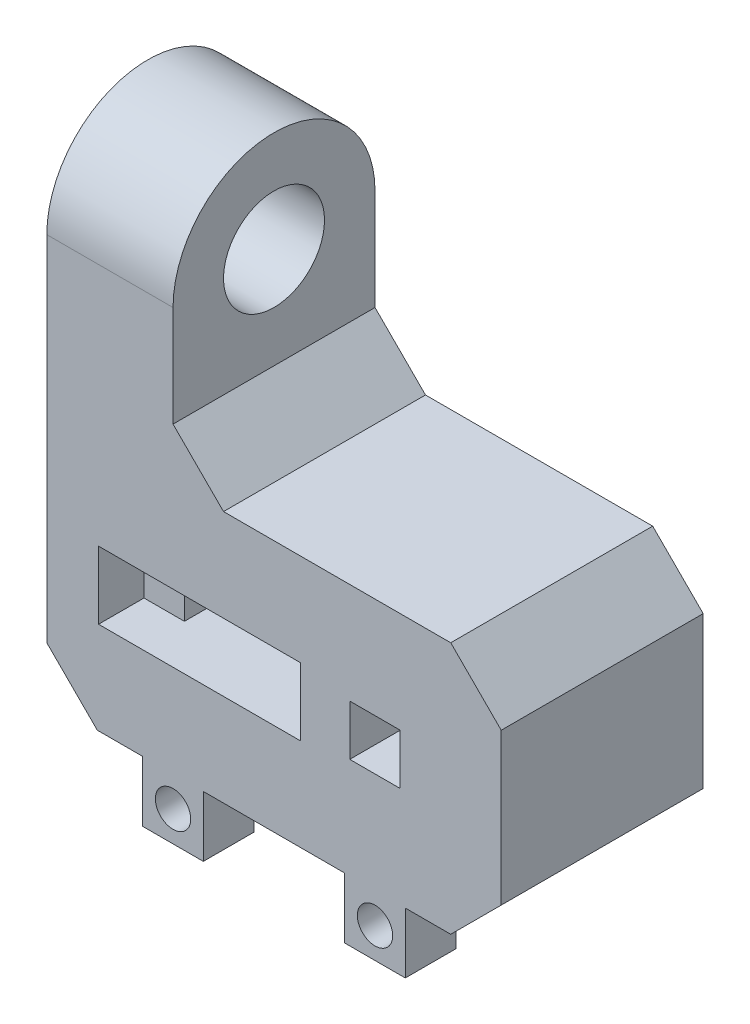
SolidWorks part; units mm, degrees
ref_plane "Front Plane" through (0, 0, 0) normal (0, 0, 1) x (1, 0, 0)
ref_plane "Top Plane" through (0, 0, 0) normal (0, 1, 0) x (1, 0, 0)
ref_plane "Right Plane" through (0, 0, 0) normal (1, 0, 0) x (0, 0, -1)
sketch "Sketch1" plane through (0, 0, 0) normal (0, 0, 1) x (1, 0, 0)
  line L1 (-90, 50) -> (0, 50)
  line L2 (-90, 50) -> (-90, 0)
  line L3 (-90, 0) -> (0, 0)
  line L4 (0, 50) -> (0, 0)
  dimension "D1" = 90
  dimension "D2" = 50
extrude "Boss-Extrude1" add sketch "Sketch1" along normal blind 40
sketch "Sketch19" plane through (0, 0, 40) normal (0, 0, 1) x (1, 0, 0)
  line L0 (-65, 25) -> (-25, 25) construction
  line L1 (-65, 25) -> (-65, 0) construction
  line L2 (-90, 0) -> (0, 0) construction
  line L3 (-65, 25) -> (-65, 50) construction
  line L4 (0, 50) -> (-90, 50) construction
  line L7 (-25, 25) -> (0, 25) construction
  line L8 (0, 0) -> (0, 50) construction
  line L9 (-65, 25) -> (-90, 25) construction
  line L10 (-90, 50) -> (-90, 0) construction
  circle A0 centre (-65, 25) radius 20
  circle A1 centre (-25, 25) radius 20
  point P10 (0, 0)
  point P11 (0, 0)
  dimension "D1" = 40
  dimension "D2" = 40
sketch "Sketch21" plane through (0, 0, 40) normal (0, 0, 1) x (1, 0, 0)
  line L1 (-30, 30) -> (-20, 30)
  line L2 (-30, 30) -> (-30, 20)
  line L3 (-30, 20) -> (-20, 20)
  line L4 (-20, 30) -> (-20, 20)
  circle A0 centre (-25, 25) radius 5
  dimension "D1" = 10
extrude "Cut-Extrude10" cut sketch "Sketch21" against normal up to surface (40 mm away) contours A0 | A0 L1 L2 | A0 L2 L3 | A0 L3 L4 | A0 L4 L1 up to face at (-45, 25, 0)
sketch "Sketch22" plane through (0, 0, 40) normal (0, 0, 1) x (1, 0, 0)
  line L0 (-79.75, 25) -> (-90, 25) construction
  line L1 (-79.75, 18.3) -> (-39.75, 18.3)
  line L2 (-79.75, 18.3) -> (-79.75, 31.7)
  line L3 (-79.75, 31.7) -> (-39.75, 31.7)
  line L4 (-39.75, 18.3) -> (-39.75, 31.7)
  line L5 (-59.75, 18.3) -> (-59.75, 0) construction
  line L6 (-90, 0) -> (0, 0) construction
  line L7 (-59.75, 31.7) -> (-59.75, 50) construction
  line L8 (0, 50) -> (-90, 50) construction
  point P16 (-59.75, 18.3)
  dimension "D1" = 10.25
  dimension "D3" = 13.4
  dimension "D4" = 40
extrude "Cut-Extrude11" cut sketch "Sketch22" against normal blind 9
sketch "Sketch24" plane through (0, 0, 31) normal (0, 0, 1) x (1, 0, 0)
  line L0 (-79.75, 18.3) -> (-39.75, 18.3) construction
  line L1 (-71.75, 18.3) -> (-47.75, 18.3)
  line L2 (-71.75, 18.3) -> (-71.75, 31.7)
  line L3 (-71.75, 31.7) -> (-47.75, 31.7)
  line L4 (-47.75, 18.3) -> (-47.75, 31.7)
  line L5 (-39.75, 31.7) -> (-79.75, 31.7) construction
  line L6 (-39.75, 25) -> (-47.75, 25) construction
  line L7 (-39.75, 18.3) -> (-39.75, 31.7) construction
  line L8 (-71.75, 25) -> (-79.75, 25) construction
  line L10 (-79.75, 31.7) -> (-79.75, 18.3) construction
  dimension "D1" = 24
extrude "Cut-Extrude12" cut sketch "Sketch24" against normal up to surface (31 mm away) up to face at (-45, 25, 0)
sketch "Sketch25" plane through (0, 0, 31) normal (0, 0, 1) x (1, 0, 0)
  line L0 (-46.25, 25) -> (-73.25, 25) construction
  circle A0 centre (-73.25, 25) radius 1.1
  circle A1 centre (-46.25, 25) radius 1.1
  dimension "D1" = 2.2
extrude "Cut-Extrude13" cut sketch "Sketch25" against normal up to surface (31 mm away) up to face at (-59.75, 25, 0)
ref_plane "Plane1" through (-45, 0, 0) normal (-1, 0, 0) x (0, 0, 1)
sketch "Sketch31" plane through (0, 50, 0) normal (0, 1, 0) x (1, 0, 0)
  line L0 (0, 0) -> (-90, 0) construction
  line L1 (-25, 0) -> (0, 0)
  line L2 (-25, 0) -> (-25, -40)
  line L3 (-25, -40) -> (0, -40)
  line L4 (0, 0) -> (0, -40)
  line L5 (-65, -40) -> (-90, -40) construction
  line L6 (-90, 0) -> (-65, 0)
  line L7 (-90, 0) -> (-90, -40)
  line L8 (-90, -40) -> (-65, -40)
  line L9 (-65, 0) -> (-65, -40)
  line M5 (0, 0) -> (-90, 0)
  line M6 (-90, 0) -> (-90, -40)
  line M7 (-90, -40) -> (0, -40)
  dimension "D1" = 25
extrude "Boss-Extrude2" add sketch "Sketch31" along normal blind 50 contours L9 M5 M6 M7
sketch "Sketch32" plane through (-65, 0, 0) normal (1, 0, 0) x (0, 0, -1)
  line L0 (0, 100) -> (-40, 100) construction
  line L1 (-40, 100) -> (-40, 50) construction
  line L2 (0, 100) -> (0, 50) construction
  circle A0 centre (-20, 80) radius 20
  circle A1 centre (-20, 80) radius 10
  line M3 (0, 50) -> (0, 100)
  line M4 (0, 100) -> (-40, 100)
  line M5 (-40, 100) -> (-40, 50)
  dimension "D1" = 20
extrude "Cut-Extrude15" cut sketch "Sketch32" against normal up to surface (25 mm away) contours A0 M4 M5 | A0 M3 M4 | A1 up to face at (-90, 50, 20)
chamfer "Chamfer1" distance 10 angle 45 4 edges at (0, 0, 20) (-90, 0, 20) (-65, 50, 20) (0, 50, 20)
sketch "Sketch35" plane through (-90, 0, 0) normal (-1, 0, 0) x (0, 0, 1)
  line L0 (22.1864, 25) -> (40, 25) construction
  line L1 (40, 5) -> (40, 45) construction
  line L2 (7.1864, 35) -> (22.1864, 35)
  line L3 (7.1864, 35) -> (7.1864, 15)
  line L4 (7.1864, 15) -> (22.1864, 15)
  line L5 (22.1864, 35) -> (22.1864, 15)
  line L6 (14.6864, 15) -> (14.6864, 10) construction
  line L7 (0, 10) -> (40, 10) construction
  dimension "D1" = 15
  dimension "D2" = 20
extrude "Cut-Extrude16" cut sketch "Sketch35" against normal up to surface (42.25 mm away) up to face at (-47.75, 25, 15.5)
sketch "Sketch36" plane through (0, 0, 40) normal (0, 0, 1) x (1, 0, 0)
  line L0 (-59, -12) -> (-71, -12)
  line L4 (-59, 0) -> (-59, -12)
  line L8 (-71, 0) -> (-71, -12)
  line L9 (-59, 0) -> (-71, 0)
  line L10 (-80, 0) -> (-10, 0) construction
  line L11 (-65, 25) -> (-65, -25.8642) construction
  line L12 (-25, 25) -> (-25, 0) construction
  line L13 (-31, 0) -> (-19, 0)
  line L14 (-31, 0) -> (-31, -12)
  line L15 (-31, -12) -> (-19, -12)
  line L16 (-19, 0) -> (-19, -12)
  line L17 (-71, -12) -> (-59, 0) construction
  line L18 (-31, 0) -> (-19, -12) construction
  line L19 (-31, -12) -> (-19, 0) construction
  circle A0 centre (-65, -6) radius 3.5
  circle A1 centre (-25, -6) radius 3.5
  point P11 (-65, 0)
  point P19 (-25, 0)
  point P24 (0, 0)
  line M11 (-80, 0) -> (-10, 0)
  dimension "D4" = 7
  dimension "D2" = 12
  dimension "D3" = 12
extrude "Boss-Extrude3" add sketch "Sketch36" against normal blind 10 contours L8 L0 L4 A0 M11 | L16 L14 L15 A1 M11
